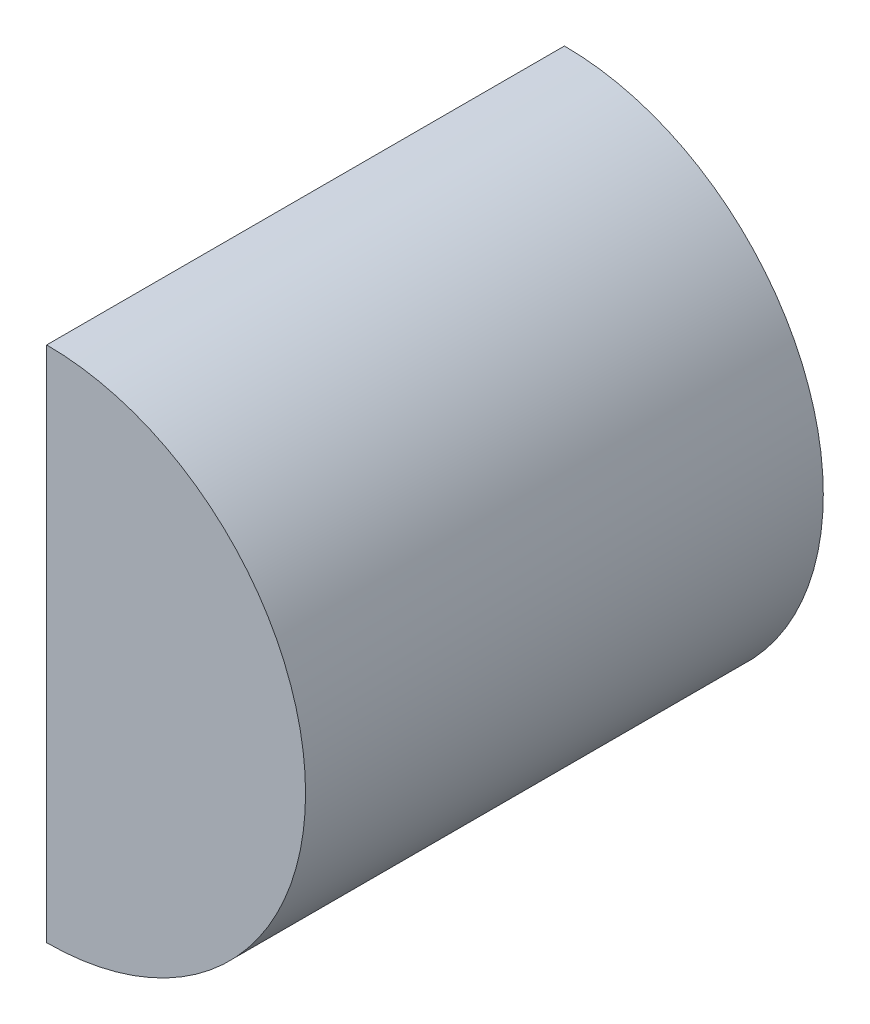
SolidWorks part; units mm, degrees
ref_plane "Alzado" through (0, 0, 0) normal (0, 0, 1) x (1, 0, 0)
ref_plane "Planta" through (0, 0, 0) normal (0, 1, 0) x (1, 0, 0)
ref_plane "Vista lateral" through (0, 0, 0) normal (1, 0, 0) x (0, 0, -1)
sketch "Croquis1" plane through (0, 0, 0) normal (0, 0, 1) x (1, 0, 0)
  line L0 (0, 25) -> (0, -25)
  arc A0 (0, -25) -> (0, 25) centre (0, 0) ccw
  dimension "D1" = 50
extrude "Saliente-Extruir1" add sketch "Croquis1" along normal blind 50
sketch "Croquis2" plane through (0, 0, 0) normal (0, 0, -1) x (-1, 0, 0)
  circle A0 centre (-10.5504, 0) radius 5
  dimension "D1" = 10
extrude "Cortar-Extruir1" cut sketch "Croquis2" against normal blind 10
